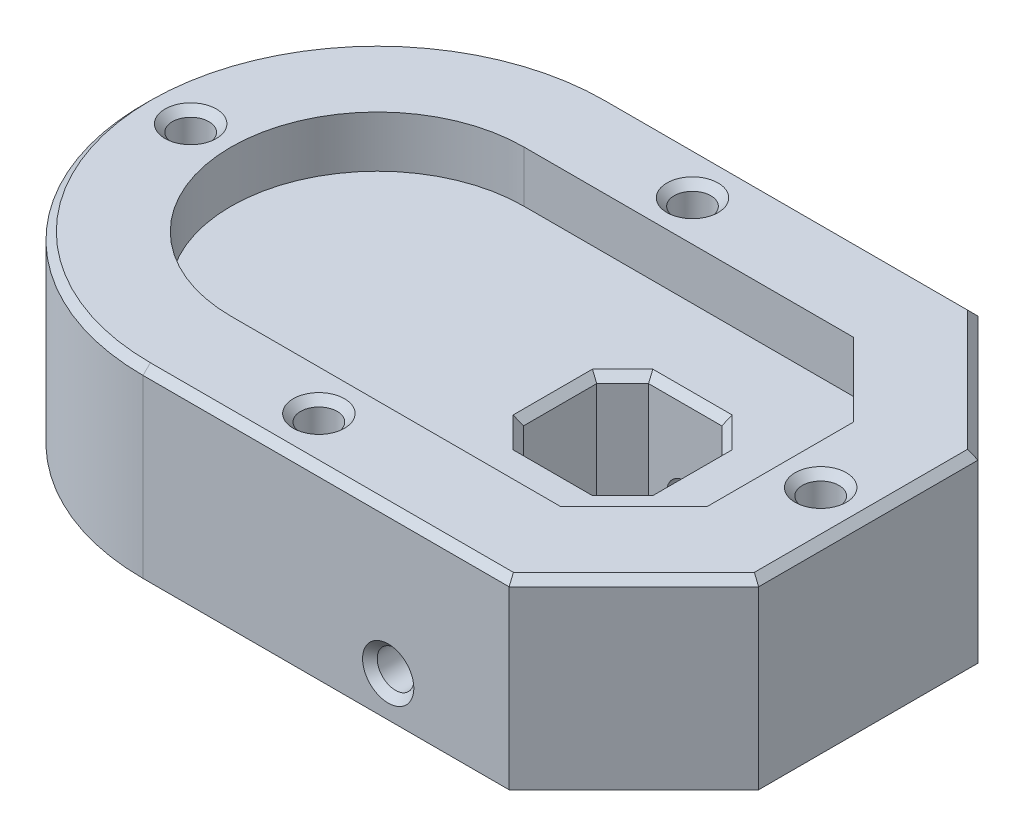
SolidWorks part; units mm, degrees
ref_plane "Front Plane" through (0, 0, 0) normal (0, 0, 1) x (1, 0, 0)
ref_plane "Top Plane" through (0, 0, 0) normal (0, 1, 0) x (1, 0, 0)
ref_plane "Right Plane" through (0, 0, 0) normal (1, 0, 0) x (0, 0, -1)
sketch "Sketch1" plane through (0, 0, 0) normal (0, 1, 0) x (1, 0, 0)
  line L0 (37.5, 10) -> (37.5, -10)
  line L1 (-37.5, 20) -> (27.5, 20)
  line L2 (-37.5, 20) -> (-37.5, -20)
  line L3 (-37.5, -20) -> (27.5, -20)
  line L4 (37.5, 10) -> (37.5, -10)
  line L5 (-37.5, 20) -> (37.5, -20) construction
  line L6 (-37.5, -20) -> (37.5, 20) construction
  line L7 (27.5, 20) -> (37.5, 10)
  line L8 (37.5, -10) -> (27.5, -20)
  arc A0 (-17.5, 20) -> (-17.5, -20) centre (-17.5, 0) ccw
  point P5 (37.5, 0)
  point P6 (37.5, 0)
  point P7 (0, 0)
  point P8 (0, 0)
  dimension "D1" = 40
  dimension "D2" = 75
  dimension "D3" = 20
  dimension "D4" = 45
  dimension "D5" = 45
  dimension "D6" = 40
  dimension "D7" = 65
extrude "Boss-Extrude1" add sketch "Sketch1" along normal blind 18 contours L1 A0 L3 L8 L0 L7
sketch "Sketch2" plane through (0, 0, 0) normal (0, -1, 0) x (1, 0, 0)
  line L0 (24.5, 5) -> (24.5, -5)
  line L1 (20.9645, 8.5355) -> (24.5, 5)
  line L2 (-17.5, 20) -> (27.5, 20) construction
  line L3 (20.9645, 8.5355) -> (10.9645, 8.5355)
  line L4 (10.9645, 8.5355) -> (7.4289, 5)
  line L5 (7.4289, 5) -> (7.4289, -5)
  line L6 (7.4289, -5) -> (10.9645, -8.5355)
  line L7 (10.9645, -8.5355) -> (20.9645, -8.5355)
  line L8 (24.5, -5) -> (20.9645, -8.5355)
  line L9 (27.5, 20) -> (27.5, -20) construction
  point P1 (0, 0)
  point P5 (24.5, 0)
  point P6 (0, 0)
  dimension "D1" = 10
  dimension "D2" = 45
  dimension "D3" = 45
  dimension "D4" = 5
  dimension "D5" = 3
extrude "Cut-Extrude1" cut sketch "Sketch2" against normal up to surface (18 mm away) up to face at (12.5, 18, 0)
sketch "Sketch3" plane through (0, 0, 20) normal (0, 0, 1) x (1, 0, 0)
  line L0 (15.9645, 3) -> (15.9645, 0) construction
  line L1 (-17.5, 0) -> (27.5, 0) construction
  line L2 (20.9645, 0) -> (10.9645, 0) construction
  circle A0 centre (15.9645, 5.5) radius 2.5
  dimension "D2" = 5
  dimension "D1" = 3
sketch "Sketch4" plane through (0, 0, 0) normal (0, -1, 0) x (1, 0, 0)
  line L0 (27.5, 20) -> (-17.5, 20)
  line L1 (-17.5, 20) -> (27.5, 20) construction
  line L2 (-17.5, -20) -> (27.5, -20)
  line L3 (27.5, -20) -> (37.5, -10)
  line L4 (37.5, -10) -> (37.5, 10)
  line L5 (27.5, 20) -> (37.5, 10)
  line L6 (37.5, 10) -> (27.5, 20) construction
  line L7 (37.5, -10) -> (37.5, 10) construction
  line L8 (27.5, -20) -> (37.5, -10) construction
  line L9 (-17.5, -20) -> (27.5, -20) construction
  arc A0 (-17.5, 20) -> (-17.5, -20) centre (-17.5, 0) ccw
  arc A1 (-17.5, 20) -> (-17.5, -20) centre (-17.5, 0) ccw construction
  point P15 (0, 0)
extrude "Extrude-Thin1" add sketch "Sketch4" against normal blind 25 thin
extrude "Cut-Extrude2" cut sketch "Sketch3" against normal through all both and the other way through all contours A0
chamfer "Chamfer1" distance 1 angle 45 24 edges at (7.4853, 25, 32) (-49.5, 25, 0) (7.4853, 25, -32) (40.9853, 25, -23.4853) (49.5, 25, 0) (40.9853, 25, 23.4853) (18.4645, 5.5, 32) (18.4645, 5.5, -32) (22.7322, 0, -6.7678) (24.5, 0, 0) (22.7322, 0, 6.7678) (15.9645, 0, 8.5355) (9.1967, 0, 6.7678) (7.4289, 0, 0) (9.1967, 0, -6.7678) (15.9645, 0, -8.5355) (22.7322, 18, -6.7678) (24.5, 18, 0) (22.7322, 18, 6.7678) (15.9645, 18, 8.5355) (9.1967, 18, 6.7678) (7.4289, 18, 0) (9.1967, 18, -6.7678) (15.9645, 18, -8.5355)
sketch "Sketch6" plane through (0, 25, 0) normal (0, 1, 0) x (1, 0, 0)
  line L0 (48.5, 0) -> (-48.5, 0) construction
  line L1 (48.5, -14.5563) -> (48.5, 14.5563) construction
  line L2 (0, 31) -> (0, 20) construction
  line L3 (0, -31) -> (0, -20) construction
  line L4 (48.5, 0) -> (37.5, 0) construction
  line L5 (-37.5, 0) -> (-48.5, 0) construction
  line L6 (32.0563, 31) -> (-17.5, 31) construction
  line L8 (-17.5, 20) -> (27.5, 20) construction
  line L9 (27.5, -20) -> (-17.5, -20) construction
  line L10 (-17.5, -31) -> (32.0563, -31) construction
  line L11 (37.5, 10) -> (37.5, -10) construction
  circle A0 centre (0, 25.5) radius 2.5
  circle A1 centre (0, -25.5) radius 2.5
  circle A2 centre (43, 0) radius 2.5
  circle A3 centre (-43, 0) radius 2.5
  arc A4 (-17.5, 31) -> (-17.5, -31) centre (-17.5, 0) ccw construction
  arc A5 (-17.5, 20) -> (-17.5, -20) centre (-17.5, 0) ccw construction
  point P9 (0, 0)
  point P15 (-48.5, 0)
  point P16 (0, 0)
  point P22 (0, 0)
  point P23 (0, 0)
  point P30 (0, 0)
  point P31 (0, 0)
  point P32 (0, 0)
  point P33 (0, 0)
  point P36 (0, 0)
  point P37 (0, 0)
  point P40 (0, 0)
  point P41 (0, 0)
  point P42 (0, 0)
  point P43 (0, 0)
  point P46 (0, 0)
  point P49 (0, 0)
  point P50 (0, 0)
  point P53 (0, 0)
  dimension "D1" = 5
extrude "Cut-Extrude3" cut sketch "Sketch6" against normal through all both and the other way through all
chamfer "Chamfer3" distance 1 angle 45 4 edges at (0, 25, 23) (-43, 25, -2.5) (0, 25, -28) (43, 25, -2.5)
